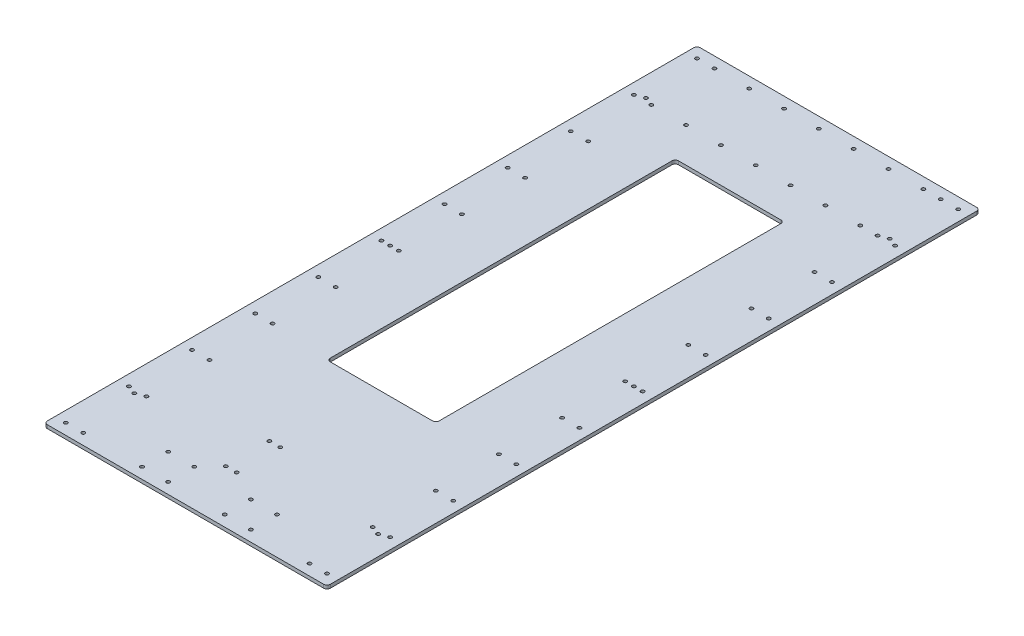
SolidWorks part; units mm, degrees
other "Markup1"
sketch "Sketch2" plane through (-130, 3.175, -300) normal (0, 1, 0) x (1, 0, 0)
ref_plane "Front Plane" through (0, 0, 0) normal (0, 0, 1) x (1, 0, 0)
ref_plane "Top Plane" through (0, 0, 0) normal (0, 1, 0) x (1, 0, 0)
ref_plane "Right Plane" through (0, 0, 0) normal (1, 0, 0) x (0, 0, -1)
sketch "Sketch1" plane through (0, 0, 0) normal (0, 1, 0) x (1, 0, 0)
  line L0 (0, 300) -> (0, -300) construction
  line L1 (-130, -300) -> (130, -300)
  line L2 (-130, -300) -> (-130, 300)
  line L3 (-130, 300) -> (130, 300)
  line L4 (130, -300) -> (130, 300)
  line L5 (-130, -300) -> (130, 300) construction
  line L6 (-130, 300) -> (130, -300) construction
  line L9 (-50, 200) -> (50, 200)
  line L10 (50, -120) -> (50, 200)
  line L11 (112, -300) -> (112, 300) construction
  line L12 (-38, -249.1372) -> (-38, -296.0221) construction
  line L13 (-130, 0) -> (130, 0) construction
  line L14 (-50, -120) -> (50, -120)
  line L15 (-50, -120) -> (-50, 200)
  line L16 (-33.8134, -231) -> (-9.1079, -231) construction
  line L17 (-91.9691, -278) -> (98.2286, -278) construction
  circle A0 centre (120, 290) radius 1.6
  circle A1 centre (120, 232) radius 1.6
  circle A2 centre (120, 174) radius 1.6
  circle A3 centre (120, 116) radius 1.6
  circle A4 centre (120, 58) radius 1.6
  circle A5 centre (120, 0) radius 1.6
  circle A6 centre (120, -58) radius 1.6
  circle A7 centre (120, -116) radius 1.6
  circle A8 centre (120, -174) radius 1.6
  circle A9 centre (120, -232) radius 1.6
  circle A10 centre (120, -290) radius 1.6
  circle A11 centre (-120, 232) radius 1.6
  circle A12 centre (-120, -290) radius 1.6
  circle A13 centre (-120, -232) radius 1.6
  circle A14 centre (-120, -174) radius 1.6
  circle A15 centre (-120, -116) radius 1.6
  circle A16 centre (-120, -58) radius 1.6
  circle A17 centre (-120, 0) radius 1.6
  circle A18 centre (-120, 58) radius 1.6
  circle A19 centre (-120, 116) radius 1.6
  circle A20 centre (-120, 174) radius 1.6
  circle A21 centre (-120, 290) radius 1.6
  circle A22 centre (112, 235) radius 1.6
  circle A23 centre (-112, 235) radius 1.6
  circle A24 centre (112, -235) radius 1.6
  circle A25 centre (-112, -235) radius 1.6
  circle A26 centre (104, 290) radius 1.6
  circle A27 centre (104, 232) radius 1.6
  circle A28 centre (104, 174) radius 1.6
  circle A29 centre (104, 116) radius 1.6
  circle A30 centre (104, 58) radius 1.6
  circle A31 centre (104, 0) radius 1.6
  circle A32 centre (104, -58) radius 1.6
  circle A33 centre (104, -116) radius 1.6
  circle A34 centre (104, -174) radius 1.6
  circle A35 centre (104, -232) radius 1.6
  circle A36 centre (104, -290) radius 1.6
  circle A37 centre (-104, -290) radius 1.6
  circle A38 centre (-104, -174) radius 1.6
  circle A39 centre (-104, -116) radius 1.6
  circle A40 centre (-104, -58) radius 1.6
  circle A41 centre (-104, 0) radius 1.6
  circle A42 centre (-104, 58) radius 1.6
  circle A43 centre (-104, 116) radius 1.6
  circle A44 centre (-104, 174) radius 1.6
  circle A45 centre (-104, 232) radius 1.6
  circle A46 centre (-104, 290) radius 1.6
  circle A47 centre (-104, -232) radius 1.6
  circle A48 centre (112, 0) radius 1.6
  circle A49 centre (-112, 0) radius 1.6
  circle A50 centre (-50, -290) radius 1.6
  circle A51 centre (-50, -266) radius 1.6
  circle A52 centre (50, -266) radius 1.6
  circle A53 centre (50, -290) radius 1.6
  circle A54 centre (-26, -290) radius 1.6
  circle A55 centre (-26, -266) radius 1.6
  circle A56 centre (26, -290) radius 1.6
  circle A57 centre (26, -266) radius 1.6
  circle A58 centre (-72, 290) radius 1.6
  circle A59 centre (-72, 232) radius 1.6
  circle A60 centre (-40, 290) radius 1.6
  circle A61 centre (-40, 232) radius 1.6
  circle A62 centre (-8, 290) radius 1.6
  circle A63 centre (-8, 232) radius 1.6
  circle A64 centre (24, 290) radius 1.6
  circle A65 centre (24, 232) radius 1.6
  circle A66 centre (56, 290) radius 1.6
  circle A67 centre (56, 232) radius 1.6
  circle A68 centre (88, 290) radius 1.6
  circle A69 centre (88, 232) radius 1.6
  circle A73 centre (-12, -251) radius 1.6
  circle A75 centre (-2, -251) radius 1.6
  circle A76 centre (-12, -211) radius 1.6
  circle A77 centre (-2, -211) radius 1.6
  circle A78 centre (120, 232) radius 1.6 [skipped]
  circle A79 centre (120, 290) radius 1.6 [skipped]
  point P0 (0, 0)
  point P6 (0, 0)
  dimension "D3" = 3.2
  dimension "D7" = 3.2
  dimension "D11" = 3.2
  dimension "D17" = 3.2
  dimension "D18" = 3.2
  dimension "D19" = 3.2
  dimension "D25" = 3.2
  dimension "D21" = 3.2
  dimension "D1" = 600
  dimension "D4" = 10
  dimension "D5" = 10
  dimension "D9" = 100
  dimension "D12" = 16
  dimension "D10" = 120
  dimension "D14" = 200
  dimension "D15" = 10
  dimension "D16" = 8
  dimension "D8" = 235
  dimension "D22" = 10
  dimension "D23" = 12
  dimension "D26" = 10
  dimension "D30" = 12
  dimension "D27" = 20
  dimension "D28" = 20
  dimension "D32" = 47
  dimension "D33" = 38
  dimension "D34" = 260
  dimension "D20" = 12
  dimension "D29" = 12
  dimension "D31" = 12
  dimension "D6" = 11
  dimension "D13" = 11
  dimension "D24" = 8
extrude "Boss-Extrude1" add sketch "Sketch1" along normal blind 3.175
fillet "Fillet1" radius 3 8 edges at (50, 1.5875, -200) (-130, 1.5875, 300) (130, 1.5875, 300) (130, 1.5875, -300) (-130, 1.5875, -300) (-50, 1.5875, -200) (-50, 1.5875, 120) (50, 1.5875, 120)
equation "\"width\"=250"
equation "\"length\"= 600"
equation "\"D1@Sketch1\"=\"length\""
equation "\"m3\"= 3.2"
